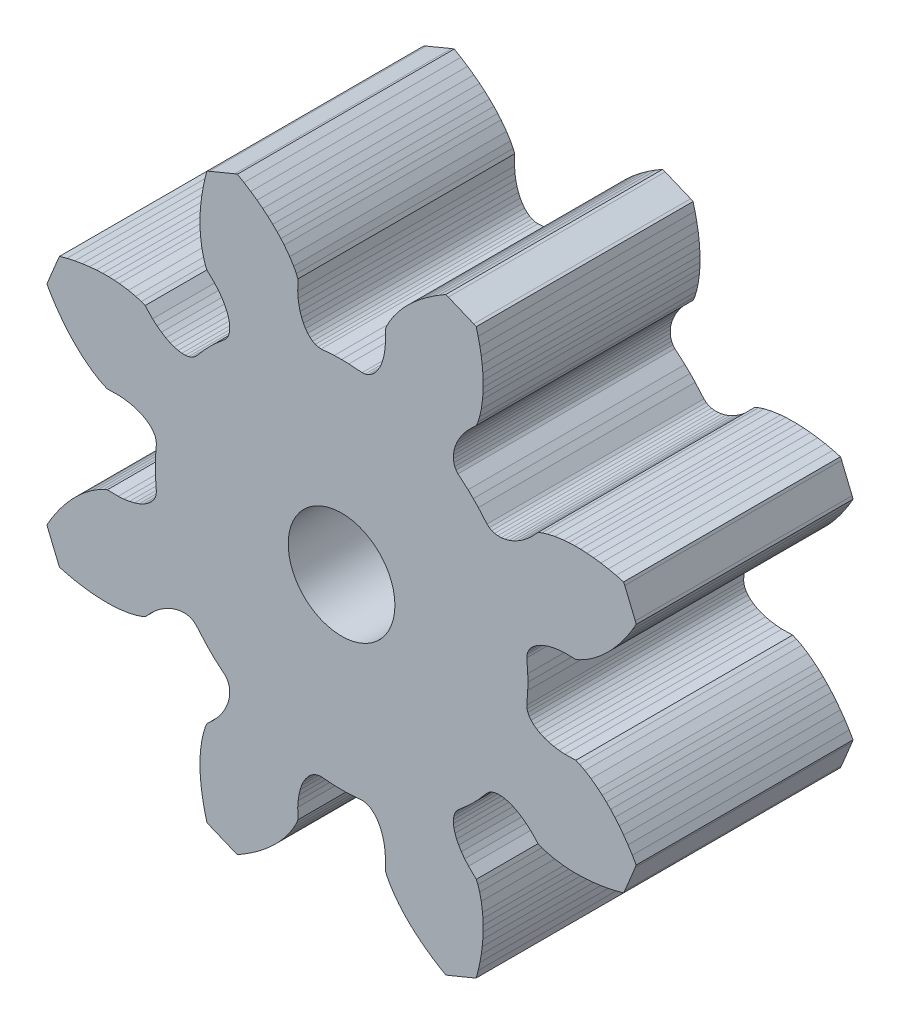
SolidWorks part; units mm, degrees
ref_plane "Front Plane" through (0, 0, 0) normal (0, 0, 1) x (1, 0, 0)
ref_plane "Top Plane" through (0, 0, 0) normal (0, 1, 0) x (1, 0, 0)
ref_plane "Right Plane" through (0, 0, 0) normal (1, 0, 0) x (0, 0, -1)
sketch "Sketch1" plane through (0, 0, 0) normal (0, 0, 1) x (1, 0, 0)
  line L472 (-0.6593, 18.6218) -> (-0.6593, 18.3271) construction
  line L473 (-0.6593, 18.3271) -> (-0.779, 17.4419) construction
  line L474 (-0.779, 17.4419) -> (-1.1197, 16.342) construction
  line L475 (-1.1197, 16.342) -> (-1.6601, 15.3477) construction
  line L476 (-1.6601, 15.3477) -> (-2.3747, 14.4808) construction
  line L477 (-2.3747, 14.4808) -> (-3.2417, 13.7653) construction
  line L478 (-3.2417, 13.7653) -> (-4.2368, 13.2249) construction
  line L479 (-4.2368, 13.2249) -> (-5.3358, 12.8842) construction
  line L480 (-5.3358, 12.8842) -> (-6.2209, 12.7645) construction
  line L481 (-6.2209, 12.7645) -> (-6.5158, 12.7645) construction
  line L482 (-6.5158, 12.7645) -> (-6.8114, 12.7645) construction
  line L483 (-6.8114, 12.7645) -> (-7.6964, 12.8842) construction
  line L484 (-7.6964, 12.8842) -> (-8.7961, 13.2249) construction
  line L485 (-8.7961, 13.2249) -> (-9.7913, 13.7653) construction
  line L486 (-9.7913, 13.7653) -> (-10.6581, 14.4808) construction
  line L487 (-10.6581, 14.4808) -> (-11.3729, 15.3477) construction
  line L488 (-11.3729, 15.3477) -> (-11.9132, 16.342) construction
  line L489 (-11.9132, 16.342) -> (-12.2541, 17.4419) construction
  line L490 (-12.2541, 17.4419) -> (-12.3729, 18.3271) construction
  line L491 (-12.3729, 18.3271) -> (-12.3729, 18.6218) construction
  line L492 (-12.3729, 18.6218) -> (-12.3729, 18.9172) construction
  line L493 (-12.3729, 18.9172) -> (-12.2541, 19.8023) construction
  line L494 (-12.2541, 19.8023) -> (-11.9132, 20.9013) construction
  line L495 (-11.9132, 20.9013) -> (-11.3729, 21.8965) construction
  line L496 (-11.3729, 21.8965) -> (-10.6581, 22.7634) construction
  line L497 (-10.6581, 22.7634) -> (-9.7913, 23.478) construction
  line L498 (-9.7913, 23.478) -> (-8.7961, 24.0184) construction
  line L499 (-8.7961, 24.0184) -> (-7.6964, 24.3591) construction
  line L500 (-7.6964, 24.3591) -> (-6.8114, 24.478) construction
  line L501 (-6.8114, 24.478) -> (-6.5158, 24.478) construction
  line L502 (-6.5158, 24.478) -> (-6.2209, 24.478) construction
  line L503 (-6.2209, 24.478) -> (-5.3358, 24.3591) construction
  line L504 (-5.3358, 24.3591) -> (-4.2368, 24.0184) construction
  line L505 (-4.2368, 24.0184) -> (-3.2417, 23.478) construction
  line L506 (-3.2417, 23.478) -> (-2.3747, 22.7634) construction
  line L507 (-2.3747, 22.7634) -> (-1.6601, 21.8965) construction
  line L508 (-1.6601, 21.8965) -> (-1.1197, 20.9013) construction
  line L509 (-1.1197, 20.9013) -> (-0.779, 19.8023) construction
  line L510 (-0.779, 19.8023) -> (-0.6593, 18.9172) construction
  line L511 (-0.6593, 18.9172) -> (-0.6593, 18.6218) construction
  line L512 (0.8049, 18.6218) -> (0.8049, 18.2532) construction
  line L513 (0.8049, 18.2532) -> (0.6559, 17.1463) construction
  line L514 (0.6559, 17.1463) -> (0.2287, 15.7724) construction
  line L515 (0.2287, 15.7724) -> (-0.4463, 14.5284) construction
  line L516 (-0.4463, 14.5284) -> (-1.34, 13.4451) construction
  line L517 (-1.34, 13.4451) -> (-2.4232, 12.5515) construction
  line L518 (-2.4232, 12.5515) -> (-3.6665, 11.8763) construction
  line L519 (-3.6665, 11.8763) -> (-5.0411, 11.4492) construction
  line L520 (-5.0411, 11.4492) -> (-6.1473, 11.3003) construction
  line L521 (-6.1473, 11.3003) -> (-6.5158, 11.3003) construction
  line L522 (-6.5158, 11.3003) -> (-6.885, 11.3003) construction
  line L523 (-6.885, 11.3003) -> (-7.9919, 11.4492) construction
  line L524 (-7.9919, 11.4492) -> (-9.3657, 11.8763) construction
  line L525 (-9.3657, 11.8763) -> (-10.6098, 12.5515) construction
  line L526 (-10.6098, 12.5515) -> (-11.693, 13.4451) construction
  line L527 (-11.693, 13.4451) -> (-12.5867, 14.5284) construction
  line L528 (-12.5867, 14.5284) -> (-13.2618, 15.7724) construction
  line L529 (-13.2618, 15.7724) -> (-13.689, 17.1463) construction
  line L530 (-13.689, 17.1463) -> (-13.837, 18.2532) construction
  line L531 (-13.837, 18.2532) -> (-13.837, 18.6218) construction
  line L532 (-13.837, 18.6218) -> (-13.837, 18.9908) construction
  line L533 (-13.837, 18.9908) -> (-13.689, 20.0979) construction
  line L534 (-13.689, 20.0979) -> (-13.2618, 21.4718) construction
  line L535 (-13.2618, 21.4718) -> (-12.5867, 22.7149) construction
  line L536 (-12.5867, 22.7149) -> (-11.693, 23.7989) construction
  line L537 (-11.693, 23.7989) -> (-10.6098, 24.6927) construction
  line L538 (-10.6098, 24.6927) -> (-9.3657, 25.3677) construction
  line L539 (-9.3657, 25.3677) -> (-7.9919, 25.794) construction
  line L540 (-7.9919, 25.794) -> (-6.885, 25.9421) construction
  line L541 (-6.885, 25.9421) -> (-6.5158, 25.9421) construction
  line L542 (-6.5158, 25.9421) -> (-6.1473, 25.9421) construction
  line L543 (-6.1473, 25.9421) -> (-5.0411, 25.794) construction
  line L544 (-5.0411, 25.794) -> (-3.6665, 25.3677) construction
  line L545 (-3.6665, 25.3677) -> (-2.4232, 24.6927) construction
  line L546 (-2.4232, 24.6927) -> (-1.34, 23.7989) construction
  line L547 (-1.34, 23.7989) -> (-0.4463, 22.7149) construction
  line L548 (-0.4463, 22.7149) -> (0.2287, 21.4718) construction
  line L549 (0.2287, 21.4718) -> (0.6559, 20.0979) construction
  line L550 (0.6559, 20.0979) -> (0.8049, 18.9908) construction
  line L551 (0.8049, 18.9908) -> (0.8049, 18.6218) construction
  line L576 (-9.7161, 12.1885) -> (-9.7564, 12.3731)
  line L577 (-9.7564, 12.3731) -> (-9.7872, 12.5499)
  line L578 (-9.7872, 12.5499) -> (-9.8096, 12.7171)
  line L579 (-9.8096, 12.7171) -> (-9.8246, 12.8763)
  line L580 (-9.8246, 12.8763) -> (-9.8316, 13.026)
  line L581 (-9.8316, 13.026) -> (-9.8325, 13.1663)
  line L582 (-9.8325, 13.1663) -> (-9.8278, 13.297)
  line L583 (-9.8278, 13.297) -> (-9.8183, 13.4183)
  line L584 (-9.8183, 13.4183) -> (-9.7888, 13.629)
  line L585 (-9.7888, 13.629) -> (-9.7501, 13.7986)
  line L586 (-9.7501, 13.7986) -> (-9.7098, 13.9285)
  line L587 (-9.7098, 13.9285) -> (-9.6724, 14.0181)
  line L588 (-9.6724, 14.0181) -> (-9.4909, 14.1939)
  line L589 (-9.4909, 14.1939) -> (-9.3999, 14.2985)
  line L590 (-9.3999, 14.2985) -> (-9.3229, 14.4023)
  line L591 (-9.3229, 14.4023) -> (-9.2604, 14.5046)
  line L592 (-9.2604, 14.5046) -> (-9.2106, 14.6045)
  line L593 (-9.2106, 14.6045) -> (-9.1732, 14.7011)
  line L594 (-9.1732, 14.7011) -> (-9.1487, 14.793)
  line L595 (-9.1487, 14.793) -> (-9.1367, 14.8802)
  line L596 (-9.1367, 14.8802) -> (-9.136, 14.961)
  line L597 (-9.136, 14.961) -> (-9.1462, 15.0347)
  line L598 (-9.1462, 15.0347) -> (-9.1678, 15.1012)
  line L599 (-9.1678, 15.1012) -> (-9.1987, 15.1599)
  line L600 (-9.1987, 15.1599) -> (-9.2438, 15.2145)
  line L601 (-9.2438, 15.2145) -> (-9.4792, 15.4174)
  line L602 (-9.4792, 15.4174) -> (-9.6019, 15.5362)
  line L603 (-9.6019, 15.5362) -> (-9.7199, 15.6591)
  line L604 (-9.7199, 15.6591) -> (-9.9236, 15.8936)
  line L605 (-9.9236, 15.8936) -> (-9.9784, 15.9395)
  line L606 (-9.9784, 15.9395) -> (-10.0361, 15.9704)
  line L607 (-10.0361, 15.9704) -> (-10.1027, 15.991)
  line L608 (-10.1027, 15.991) -> (-10.1763, 16.0014)
  line L609 (-10.1763, 16.0014) -> (-10.2572, 16.0014)
  line L610 (-10.2572, 16.0014) -> (-10.3445, 15.9887)
  line L611 (-10.3445, 15.9887) -> (-10.4364, 15.9642)
  line L612 (-10.4364, 15.9642) -> (-10.5329, 15.9276)
  line L613 (-10.5329, 15.9276) -> (-10.6327, 15.8777)
  line L614 (-10.6327, 15.8777) -> (-10.7349, 15.8143)
  line L615 (-10.7349, 15.8143) -> (-10.8396, 15.7375)
  line L616 (-10.8396, 15.7375) -> (-10.9435, 15.6472)
  line L617 (-10.9435, 15.6472) -> (-11.1193, 15.465)
  line L618 (-11.1193, 15.465) -> (-11.2089, 15.4285)
  line L619 (-11.2089, 15.4285) -> (-11.3388, 15.3873)
  line L620 (-11.3388, 15.3873) -> (-11.5084, 15.3484)
  line L621 (-11.5084, 15.3484) -> (-11.72, 15.3191)
  line L622 (-11.72, 15.3191) -> (-11.8405, 15.3096)
  line L623 (-11.8405, 15.3096) -> (-11.9711, 15.3049)
  line L624 (-11.9711, 15.3049) -> (-12.1113, 15.3065)
  line L625 (-12.1113, 15.3065) -> (-12.2611, 15.3135)
  line L626 (-12.2611, 15.3135) -> (-12.4203, 15.3278)
  line L627 (-12.4203, 15.3278) -> (-12.5883, 15.35)
  line L628 (-12.5883, 15.35) -> (-12.7643, 15.381)
  line L629 (-12.7643, 15.381) -> (-12.9487, 15.4213)
  line L630 (-12.9487, 15.4213) -> (-13.1224, 15.4673)
  line L631 (-13.1224, 15.4673) -> (-13.1503, 15.5259)
  line L632 (-13.1503, 15.5259) -> (-13.3965, 16.1201)
  line L633 (-13.3965, 16.1201) -> (-13.418, 16.1805)
  line L634 (-13.418, 16.1805) -> (-13.3277, 16.3357)
  line L635 (-13.3277, 16.3357) -> (-13.2264, 16.495)
  line L636 (-13.2264, 16.495) -> (-13.1232, 16.6415)
  line L637 (-13.1232, 16.6415) -> (-13.0201, 16.7755)
  line L638 (-13.0201, 16.7755) -> (-12.9179, 16.8983)
  line L639 (-12.9179, 16.8983) -> (-12.8173, 17.0093)
  line L640 (-12.8173, 17.0093) -> (-12.7184, 17.109)
  line L641 (-12.7184, 17.109) -> (-12.6224, 17.1986)
  line L642 (-12.6224, 17.1986) -> (-12.5306, 17.2771)
  line L643 (-12.5306, 17.2771) -> (-12.3609, 17.4055)
  line L644 (-12.3609, 17.4055) -> (-12.2135, 17.4982)
  line L645 (-12.2135, 17.4982) -> (-12.0924, 17.5606)
  line L646 (-12.0924, 17.5606) -> (-12.0035, 17.5989)
  line L647 (-12.0035, 17.5989) -> (-11.75, 17.5939)
  line L648 (-11.75, 17.5939) -> (-11.6122, 17.6043)
  line L649 (-11.6122, 17.6043) -> (-11.4847, 17.6234)
  line L650 (-11.4847, 17.6234) -> (-11.3672, 17.651)
  line L651 (-11.3672, 17.651) -> (-11.2619, 17.6858)
  line L652 (-11.2619, 17.6858) -> (-11.1677, 17.7278)
  line L653 (-11.1677, 17.7278) -> (-11.0853, 17.7763)
  line L654 (-11.0853, 17.7763) -> (-11.0146, 17.8285)
  line L655 (-11.0146, 17.8285) -> (-10.9569, 17.8856)
  line L656 (-10.9569, 17.8856) -> (-10.9116, 17.9459)
  line L657 (-10.9116, 17.9459) -> (-10.88, 18.0075)
  line L658 (-10.88, 18.0075) -> (-10.861, 18.0702)
  line L659 (-10.861, 18.0702) -> (-10.8547, 18.1408)
  line L660 (-10.8547, 18.1408) -> (-10.8769, 18.4513)
  line L661 (-10.8769, 18.4513) -> (-10.88, 18.6218)
  line L662 (-10.88, 18.6218) -> (-10.8769, 18.7919)
  line L663 (-10.8769, 18.7919) -> (-10.8547, 19.1018)
  line L664 (-10.8547, 19.1018) -> (-10.861, 19.1731)
  line L665 (-10.861, 19.1731) -> (-10.88, 19.2358)
  line L666 (-10.88, 19.2358) -> (-10.9116, 19.2977)
  line L667 (-10.9116, 19.2977) -> (-10.9569, 19.3579)
  line L668 (-10.9569, 19.3579) -> (-11.0146, 19.4141)
  line L669 (-11.0146, 19.4141) -> (-11.0853, 19.4673)
  line L670 (-11.0853, 19.4673) -> (-11.1677, 19.5147)
  line L671 (-11.1677, 19.5147) -> (-11.2619, 19.5566)
  line L672 (-11.2619, 19.5566) -> (-11.3672, 19.5924)
  line L673 (-11.3672, 19.5924) -> (-11.4847, 19.6202)
  line L674 (-11.4847, 19.6202) -> (-11.6122, 19.639)
  line L675 (-11.6122, 19.639) -> (-11.75, 19.6485)
  line L676 (-11.75, 19.6485) -> (-12.0035, 19.6447)
  line L677 (-12.0035, 19.6447) -> (-12.0924, 19.6818)
  line L678 (-12.0924, 19.6818) -> (-12.2135, 19.7453)
  line L679 (-12.2135, 19.7453) -> (-12.3609, 19.8381)
  line L680 (-12.3609, 19.8381) -> (-12.5306, 19.9664)
  line L681 (-12.5306, 19.9664) -> (-12.6224, 20.0447)
  line L682 (-12.6224, 20.0447) -> (-12.7184, 20.1344)
  line L683 (-12.7184, 20.1344) -> (-12.8173, 20.2333)
  line L684 (-12.8173, 20.2333) -> (-12.9179, 20.3443)
  line L685 (-12.9179, 20.3443) -> (-13.0201, 20.4678)
  line L686 (-13.0201, 20.4678) -> (-13.1232, 20.6018)
  line L687 (-13.1232, 20.6018) -> (-13.2264, 20.7484)
  line L688 (-13.2264, 20.7484) -> (-13.3277, 20.9076)
  line L689 (-13.3277, 20.9076) -> (-13.418, 21.0621)
  line L690 (-13.418, 21.0621) -> (-13.3965, 21.1233)
  line L691 (-13.3965, 21.1233) -> (-13.1503, 21.7181)
  line L692 (-13.1503, 21.7181) -> (-13.1224, 21.776)
  line L693 (-13.1224, 21.776) -> (-12.9487, 21.822)
  line L694 (-12.9487, 21.822) -> (-12.7643, 21.8624)
  line L695 (-12.7643, 21.8624) -> (-12.5883, 21.8934)
  line L696 (-12.5883, 21.8934) -> (-12.4203, 21.9154)
  line L697 (-12.4203, 21.9154) -> (-12.2611, 21.9298)
  line L698 (-12.2611, 21.9298) -> (-12.1113, 21.9368)
  line L699 (-12.1113, 21.9368) -> (-11.9711, 21.9376)
  line L700 (-11.9711, 21.9376) -> (-11.8405, 21.933)
  line L701 (-11.8405, 21.933) -> (-11.72, 21.9242)
  line L702 (-11.72, 21.9242) -> (-11.5084, 21.894)
  line L703 (-11.5084, 21.894) -> (-11.3388, 21.8562)
  line L704 (-11.3388, 21.8562) -> (-11.2089, 21.815)
  line L705 (-11.2089, 21.815) -> (-11.1193, 21.7785)
  line L706 (-11.1193, 21.7785) -> (-10.9435, 21.5962)
  line L707 (-10.9435, 21.5962) -> (-10.8396, 21.5058)
  line L708 (-10.8396, 21.5058) -> (-10.7349, 21.429)
  line L709 (-10.7349, 21.429) -> (-10.6327, 21.3656)
  line L710 (-10.6327, 21.3656) -> (-10.5329, 21.3158)
  line L711 (-10.5329, 21.3158) -> (-10.4364, 21.2784)
  line L712 (-10.4364, 21.2784) -> (-10.3445, 21.2547)
  line L713 (-10.3445, 21.2547) -> (-10.2572, 21.242)
  line L714 (-10.2572, 21.242) -> (-10.1763, 21.2413)
  line L715 (-10.1763, 21.2413) -> (-10.1027, 21.2522)
  line L716 (-10.1027, 21.2522) -> (-10.0361, 21.2728)
  line L717 (-10.0361, 21.2728) -> (-9.9784, 21.3038)
  line L718 (-9.9784, 21.3038) -> (-9.9236, 21.3498)
  line L719 (-9.9236, 21.3498) -> (-9.7199, 21.5842)
  line L720 (-9.7199, 21.5842) -> (-9.6019, 21.7072)
  line L721 (-9.6019, 21.7072) -> (-9.4792, 21.8252)
  line L722 (-9.4792, 21.8252) -> (-9.2438, 22.0289)
  line L723 (-9.2438, 22.0289) -> (-9.1987, 22.0836)
  line L724 (-9.1987, 22.0836) -> (-9.1678, 22.1412)
  line L725 (-9.1678, 22.1412) -> (-9.1462, 22.2078)
  line L726 (-9.1462, 22.2078) -> (-9.136, 22.2825)
  line L727 (-9.136, 22.2825) -> (-9.1367, 22.3632)
  line L728 (-9.1367, 22.3632) -> (-9.1487, 22.4504)
  line L729 (-9.1487, 22.4504) -> (-9.1732, 22.5423)
  line L730 (-9.1732, 22.5423) -> (-9.2106, 22.6388)
  line L731 (-9.2106, 22.6388) -> (-9.2604, 22.7389)
  line L732 (-9.2604, 22.7389) -> (-9.3229, 22.841)
  line L733 (-9.3229, 22.841) -> (-9.3999, 22.9448)
  line L734 (-9.3999, 22.9448) -> (-9.4909, 23.0494)
  line L735 (-9.4909, 23.0494) -> (-9.6724, 23.2254)
  line L736 (-9.6724, 23.2254) -> (-9.7098, 23.3147)
  line L737 (-9.7098, 23.3147) -> (-9.7501, 23.4447)
  line L738 (-9.7501, 23.4447) -> (-9.7888, 23.6143)
  line L739 (-9.7888, 23.6143) -> (-9.8183, 23.8252)
  line L740 (-9.8183, 23.8252) -> (-9.8278, 23.9455)
  line L741 (-9.8278, 23.9455) -> (-9.8325, 24.0771)
  line L742 (-9.8325, 24.0771) -> (-9.8316, 24.2175)
  line L743 (-9.8316, 24.2175) -> (-9.8246, 24.3663)
  line L744 (-9.8246, 24.3663) -> (-9.8096, 24.5263)
  line L745 (-9.8096, 24.5263) -> (-9.7872, 24.6934)
  line L746 (-9.7872, 24.6934) -> (-9.7564, 24.8701)
  line L747 (-9.7564, 24.8701) -> (-9.7161, 25.0542)
  line L748 (-9.7161, 25.0542) -> (-9.6708, 25.2284)
  line L749 (-9.6708, 25.2284) -> (-9.613, 25.2561)
  line L750 (-9.613, 25.2561) -> (-9.0178, 25.5027)
  line L751 (-9.0178, 25.5027) -> (-8.9571, 25.5238)
  line L752 (-8.9571, 25.5238) -> (-8.8017, 25.4329)
  line L753 (-8.8017, 25.4329) -> (-8.6432, 25.3314)
  line L754 (-8.6432, 25.3314) -> (-8.4966, 25.2284)
  line L755 (-8.4966, 25.2284) -> (-8.3619, 25.1262)
  line L756 (-8.3619, 25.1262) -> (-8.2391, 25.023)
  line L757 (-8.2391, 25.023) -> (-8.1283, 24.9224)
  line L758 (-8.1283, 24.9224) -> (-8.0284, 24.8243)
  line L759 (-8.0284, 24.8243) -> (-7.9387, 24.7283)
  line L760 (-7.9387, 24.7283) -> (-7.8603, 24.6365)
  line L761 (-7.8603, 24.6365) -> (-7.732, 24.466)
  line L762 (-7.732, 24.466) -> (-7.6393, 24.3188)
  line L763 (-7.6393, 24.3188) -> (-7.5767, 24.1983)
  line L764 (-7.5767, 24.1983) -> (-7.5394, 24.1086)
  line L765 (-7.5394, 24.1086) -> (-7.5434, 23.856)
  line L766 (-7.5434, 23.856) -> (-7.5339, 23.7183)
  line L767 (-7.5339, 23.7183) -> (-7.514, 23.5897)
  line L768 (-7.514, 23.5897) -> (-7.4873, 23.4733)
  line L769 (-7.4873, 23.4733) -> (-7.4515, 23.367)
  line L770 (-7.4515, 23.367) -> (-7.4096, 23.2728)
  line L771 (-7.4096, 23.2728) -> (-7.3611, 23.1904)
  line L772 (-7.3611, 23.1904) -> (-7.3089, 23.1198)
  line L773 (-7.3089, 23.1198) -> (-7.2517, 23.0628)
  line L774 (-7.2517, 23.0628) -> (-7.1923, 23.0178)
  line L775 (-7.1923, 23.0178) -> (-7.1306, 22.9851)
  line L776 (-7.1306, 22.9851) -> (-7.0671, 22.9663)
  line L777 (-7.0671, 22.9663) -> (-6.9967, 22.9597)
  line L778 (-6.9967, 22.9597) -> (-6.6868, 22.982)
  line L779 (-6.6868, 22.982) -> (-6.5158, 22.9851)
  line L780 (-6.5158, 22.9851) -> (-6.3455, 22.982)
  line L781 (-6.3455, 22.982) -> (-6.0354, 22.9597)
  line L782 (-6.0354, 22.9597) -> (-5.965, 22.9663)
  line L783 (-5.965, 22.9663) -> (-5.9016, 22.9851)
  line L784 (-5.9016, 22.9851) -> (-5.8397, 23.0178)
  line L785 (-5.8397, 23.0178) -> (-5.7806, 23.0628)
  line L786 (-5.7806, 23.0628) -> (-5.7233, 23.1198)
  line L787 (-5.7233, 23.1198) -> (-5.6703, 23.1904)
  line L788 (-5.6703, 23.1904) -> (-5.6227, 23.2728)
  line L789 (-5.6227, 23.2728) -> (-5.5808, 23.367)
  line L790 (-5.5808, 23.367) -> (-5.545, 23.4733)
  line L791 (-5.545, 23.4733) -> (-5.5174, 23.5897)
  line L792 (-5.5174, 23.5897) -> (-5.4984, 23.7183)
  line L793 (-5.4984, 23.7183) -> (-5.4888, 23.856)
  line L794 (-5.4888, 23.856) -> (-5.4928, 24.1086)
  line L795 (-5.4928, 24.1086) -> (-5.4556, 24.1983)
  line L796 (-5.4556, 24.1983) -> (-5.3928, 24.3188)
  line L797 (-5.3928, 24.3188) -> (-5.3002, 24.466)
  line L798 (-5.3002, 24.466) -> (-5.172, 24.6365)
  line L799 (-5.172, 24.6365) -> (-5.0927, 24.7283)
  line L800 (-5.0927, 24.7283) -> (-5.0037, 24.8243)
  line L801 (-5.0037, 24.8243) -> (-4.904, 24.9224)
  line L802 (-4.904, 24.9224) -> (-4.793, 25.023)
  line L803 (-4.793, 25.023) -> (-4.6703, 25.1262)
  line L804 (-4.6703, 25.1262) -> (-4.5356, 25.2284)
  line L805 (-4.5356, 25.2284) -> (-4.389, 25.3314)
  line L806 (-4.389, 25.3314) -> (-4.2306, 25.4329)
  line L807 (-4.2306, 25.4329) -> (-4.0752, 25.5238)
  line L808 (-4.0752, 25.5238) -> (-4.015, 25.5027)
  line L809 (-4.015, 25.5027) -> (-3.42, 25.2561)
  line L810 (-3.42, 25.2561) -> (-3.3614, 25.2284)
  line L811 (-3.3614, 25.2284) -> (-3.3162, 25.0542)
  line L812 (-3.3162, 25.0542) -> (-3.2758, 24.8701)
  line L813 (-3.2758, 24.8701) -> (-3.2442, 24.6934)
  line L814 (-3.2442, 24.6934) -> (-3.2218, 24.5263)
  line L815 (-3.2218, 24.5263) -> (-3.2076, 24.3663)
  line L816 (-3.2076, 24.3663) -> (-3.2005, 24.2175)
  line L817 (-3.2005, 24.2175) -> (-3.1998, 24.0771)
  line L818 (-3.1998, 24.0771) -> (-3.2044, 23.9455)
  line L819 (-3.2044, 23.9455) -> (-3.2139, 23.8252)
  line L820 (-3.2139, 23.8252) -> (-3.2433, 23.6143)
  line L821 (-3.2433, 23.6143) -> (-3.2812, 23.4447)
  line L822 (-3.2812, 23.4447) -> (-3.3224, 23.3147)
  line L823 (-3.3224, 23.3147) -> (-3.3598, 23.2254)
  line L824 (-3.3598, 23.2254) -> (-3.5411, 23.0494)
  line L825 (-3.5411, 23.0494) -> (-3.6323, 22.9448)
  line L826 (-3.6323, 22.9448) -> (-3.7084, 22.841)
  line L827 (-3.7084, 22.841) -> (-3.7717, 22.7389)
  line L828 (-3.7717, 22.7389) -> (-3.8216, 22.6388)
  line L829 (-3.8216, 22.6388) -> (-3.859, 22.5423)
  line L830 (-3.859, 22.5423) -> (-3.8835, 22.4504)
  line L831 (-3.8835, 22.4504) -> (-3.8955, 22.3632)
  line L832 (-3.8955, 22.3632) -> (-3.8961, 22.2825)
  line L833 (-3.8961, 22.2825) -> (-3.8859, 22.2078)
  line L834 (-3.8859, 22.2078) -> (-3.8644, 22.1412)
  line L835 (-3.8644, 22.1412) -> (-3.8336, 22.0836)
  line L836 (-3.8336, 22.0836) -> (-3.7883, 22.0289)
  line L837 (-3.7883, 22.0289) -> (-3.553, 21.8252)
  line L838 (-3.553, 21.8252) -> (-3.4304, 21.7072)
  line L839 (-3.4304, 21.7072) -> (-3.3124, 21.5842)
  line L840 (-3.3124, 21.5842) -> (-3.1086, 21.3498)
  line L841 (-3.1086, 21.3498) -> (-3.0539, 21.3038)
  line L842 (-3.0539, 21.3038) -> (-2.996, 21.2728)
  line L843 (-2.996, 21.2728) -> (-2.9296, 21.2522)
  line L844 (-2.9296, 21.2522) -> (-2.856, 21.2413)
  line L845 (-2.856, 21.2413) -> (-2.7742, 21.242)
  line L846 (-2.7742, 21.242) -> (-2.6877, 21.2547)
  line L847 (-2.6877, 21.2547) -> (-2.595, 21.2784)
  line L848 (-2.595, 21.2784) -> (-2.4993, 21.3158)
  line L849 (-2.4993, 21.3158) -> (-2.3996, 21.3656)
  line L850 (-2.3996, 21.3656) -> (-2.2964, 21.429)
  line L851 (-2.2964, 21.429) -> (-2.1926, 21.5058)
  line L852 (-2.1926, 21.5058) -> (-2.0879, 21.5962)
  line L853 (-2.0879, 21.5962) -> (-1.9129, 21.7785)
  line L854 (-1.9129, 21.7785) -> (-1.8234, 21.815)
  line L855 (-1.8234, 21.815) -> (-1.6934, 21.8562)
  line L856 (-1.6934, 21.8562) -> (-1.523, 21.894)
  line L857 (-1.523, 21.894) -> (-1.3122, 21.9242)
  line L858 (-1.3122, 21.9242) -> (-1.1917, 21.933)
  line L859 (-1.1917, 21.933) -> (-1.0612, 21.9376)
  line L860 (-1.0612, 21.9376) -> (-0.9208, 21.9368)
  line L861 (-0.9208, 21.9368) -> (-0.7711, 21.9298)
  line L862 (-0.7711, 21.9298) -> (-0.6111, 21.9154)
  line L863 (-0.6111, 21.9154) -> (-0.4438, 21.8934)
  line L864 (-0.4438, 21.8934) -> (-0.268, 21.8624)
  line L865 (-0.268, 21.8624) -> (-0.0834, 21.822)
  line L866 (-0.0834, 21.822) -> (0.0903, 21.776)
  line L867 (0.0903, 21.776) -> (0.118, 21.7181)
  line L868 (0.118, 21.7181) -> (0.3642, 21.1233)
  line L869 (0.3642, 21.1233) -> (0.3857, 21.0621)
  line L870 (0.3857, 21.0621) -> (0.2955, 20.9076)
  line L871 (0.2955, 20.9076) -> (0.1941, 20.7484)
  line L872 (0.1941, 20.7484) -> (0.091, 20.6018)
  line L873 (0.091, 20.6018) -> (-0.012, 20.4678)
  line L874 (-0.012, 20.4678) -> (-0.1142, 20.3443)
  line L875 (-0.1142, 20.3443) -> (-0.2148, 20.2333)
  line L876 (-0.2148, 20.2333) -> (-0.3139, 20.1344)
  line L877 (-0.3139, 20.1344) -> (-0.4098, 20.0447)
  line L878 (-0.4098, 20.0447) -> (-0.5017, 19.9664)
  line L879 (-0.5017, 19.9664) -> (-0.6712, 19.8381)
  line L880 (-0.6712, 19.8381) -> (-0.8187, 19.7453)
  line L881 (-0.8187, 19.7453) -> (-0.9398, 19.6818)
  line L882 (-0.9398, 19.6818) -> (-1.0286, 19.6447)
  line L883 (-1.0286, 19.6447) -> (-1.2823, 19.6485)
  line L884 (-1.2823, 19.6485) -> (-1.42, 19.639)
  line L885 (-1.42, 19.639) -> (-1.5475, 19.6202)
  line L886 (-1.5475, 19.6202) -> (-1.6648, 19.5924)
  line L887 (-1.6648, 19.5924) -> (-1.7702, 19.5566)
  line L888 (-1.7702, 19.5566) -> (-1.8646, 19.5147)
  line L889 (-1.8646, 19.5147) -> (-1.947, 19.4673)
  line L890 (-1.947, 19.4673) -> (-2.0175, 19.4141)
  line L891 (-2.0175, 19.4141) -> (-2.0753, 19.3579)
  line L892 (-2.0753, 19.3579) -> (-2.1197, 19.2977)
  line L893 (-2.1197, 19.2977) -> (-2.1522, 19.2358)
  line L894 (-2.1522, 19.2358) -> (-2.1713, 19.1731)
  line L895 (-2.1713, 19.1731) -> (-2.1776, 19.1018)
  line L896 (-2.1776, 19.1018) -> (-2.1552, 18.7919)
  line L897 (-2.1552, 18.7919) -> (-2.1522, 18.6218)
  line L898 (-2.1522, 18.6218) -> (-2.1552, 18.4513)
  line L899 (-2.1552, 18.4513) -> (-2.1776, 18.1408)
  line L900 (-2.1776, 18.1408) -> (-2.1713, 18.0702)
  line L901 (-2.1713, 18.0702) -> (-2.1522, 18.0075)
  line L902 (-2.1522, 18.0075) -> (-2.1197, 17.9459)
  line L903 (-2.1197, 17.9459) -> (-2.0753, 17.8856)
  line L904 (-2.0753, 17.8856) -> (-2.0175, 17.8285)
  line L905 (-2.0175, 17.8285) -> (-1.947, 17.7763)
  line L906 (-1.947, 17.7763) -> (-1.8646, 17.7278)
  line L907 (-1.8646, 17.7278) -> (-1.7702, 17.6858)
  line L908 (-1.7702, 17.6858) -> (-1.6648, 17.651)
  line L909 (-1.6648, 17.651) -> (-1.5475, 17.6234)
  line L910 (-1.5475, 17.6234) -> (-1.42, 17.6043)
  line L911 (-1.42, 17.6043) -> (-1.2823, 17.5939)
  line L912 (-1.2823, 17.5939) -> (-1.0286, 17.5989)
  line L913 (-1.0286, 17.5989) -> (-0.9398, 17.5606)
  line L914 (-0.9398, 17.5606) -> (-0.8187, 17.4982)
  line L915 (-0.8187, 17.4982) -> (-0.6712, 17.4055)
  line L916 (-0.6712, 17.4055) -> (-0.5017, 17.2771)
  line L917 (-0.5017, 17.2771) -> (-0.4098, 17.1986)
  line L918 (-0.4098, 17.1986) -> (-0.3139, 17.109)
  line L919 (-0.3139, 17.109) -> (-0.2148, 17.0093)
  line L920 (-0.2148, 17.0093) -> (-0.1142, 16.8983)
  line L921 (-0.1142, 16.8983) -> (-0.012, 16.7755)
  line L922 (-0.012, 16.7755) -> (0.091, 16.6415)
  line L923 (0.091, 16.6415) -> (0.1941, 16.495)
  line L924 (0.1941, 16.495) -> (0.2955, 16.3357)
  line L925 (0.2955, 16.3357) -> (0.3857, 16.1805)
  line L926 (0.3857, 16.1805) -> (0.3642, 16.1201)
  line L927 (0.3642, 16.1201) -> (0.118, 15.5259)
  line L928 (0.118, 15.5259) -> (0.0903, 15.4673)
  line L929 (0.0903, 15.4673) -> (-0.0834, 15.4213)
  line L930 (-0.0834, 15.4213) -> (-0.268, 15.381)
  line L931 (-0.268, 15.381) -> (-0.4438, 15.35)
  line L932 (-0.4438, 15.35) -> (-0.6111, 15.3278)
  line L933 (-0.6111, 15.3278) -> (-0.7711, 15.3135)
  line L934 (-0.7711, 15.3135) -> (-0.9208, 15.3065)
  line L935 (-0.9208, 15.3065) -> (-1.0612, 15.3049)
  line L936 (-1.0612, 15.3049) -> (-1.1917, 15.3096)
  line L937 (-1.1917, 15.3096) -> (-1.3122, 15.3191)
  line L938 (-1.3122, 15.3191) -> (-1.523, 15.3484)
  line L939 (-1.523, 15.3484) -> (-1.6934, 15.3873)
  line L940 (-1.6934, 15.3873) -> (-1.8234, 15.4285)
  line L941 (-1.8234, 15.4285) -> (-1.9129, 15.465)
  line L942 (-1.9129, 15.465) -> (-2.0879, 15.6472)
  line L943 (-2.0879, 15.6472) -> (-2.1926, 15.7375)
  line L944 (-2.1926, 15.7375) -> (-2.2964, 15.8143)
  line L945 (-2.2964, 15.8143) -> (-2.3996, 15.8777)
  line L946 (-2.3996, 15.8777) -> (-2.4993, 15.9276)
  line L947 (-2.4993, 15.9276) -> (-2.595, 15.9642)
  line L948 (-2.595, 15.9642) -> (-2.6877, 15.9887)
  line L949 (-2.6877, 15.9887) -> (-2.7742, 16.0014)
  line L950 (-2.7742, 16.0014) -> (-2.856, 16.0014)
  line L951 (-2.856, 16.0014) -> (-2.9296, 15.991)
  line L952 (-2.9296, 15.991) -> (-2.996, 15.9704)
  line L953 (-2.996, 15.9704) -> (-3.0539, 15.9395)
  line L954 (-3.0539, 15.9395) -> (-3.1086, 15.8936)
  line L955 (-3.1086, 15.8936) -> (-3.3124, 15.6591)
  line L956 (-3.3124, 15.6591) -> (-3.4304, 15.5362)
  line L957 (-3.4304, 15.5362) -> (-3.553, 15.4174)
  line L958 (-3.553, 15.4174) -> (-3.7883, 15.2145)
  line L959 (-3.7883, 15.2145) -> (-3.8336, 15.1599)
  line L960 (-3.8336, 15.1599) -> (-3.8644, 15.1012)
  line L961 (-3.8644, 15.1012) -> (-3.8859, 15.0347)
  line L962 (-3.8859, 15.0347) -> (-3.8961, 14.961)
  line L963 (-3.8961, 14.961) -> (-3.8955, 14.8802)
  line L964 (-3.8955, 14.8802) -> (-3.8835, 14.793)
  line L965 (-3.8835, 14.793) -> (-3.859, 14.7011)
  line L966 (-3.859, 14.7011) -> (-3.8216, 14.6045)
  line L967 (-3.8216, 14.6045) -> (-3.7717, 14.5046)
  line L968 (-3.7717, 14.5046) -> (-3.7084, 14.4023)
  line L969 (-3.7084, 14.4023) -> (-3.6323, 14.2985)
  line L970 (-3.6323, 14.2985) -> (-3.5411, 14.1939)
  line L971 (-3.5411, 14.1939) -> (-3.3598, 14.0181)
  line L972 (-3.3598, 14.0181) -> (-3.3224, 13.9285)
  line L973 (-3.3224, 13.9285) -> (-3.2812, 13.7986)
  line L974 (-3.2812, 13.7986) -> (-3.2433, 13.629)
  line L975 (-3.2433, 13.629) -> (-3.2139, 13.4183)
  line L976 (-3.2139, 13.4183) -> (-3.2044, 13.297)
  line L977 (-3.2044, 13.297) -> (-3.1998, 13.1663)
  line L978 (-3.1998, 13.1663) -> (-3.2005, 13.026)
  line L979 (-3.2005, 13.026) -> (-3.2076, 12.8763)
  line L980 (-3.2076, 12.8763) -> (-3.2218, 12.7171)
  line L981 (-3.2218, 12.7171) -> (-3.2442, 12.5499)
  line L982 (-3.2442, 12.5499) -> (-3.2758, 12.3731)
  line L983 (-3.2758, 12.3731) -> (-3.3162, 12.1885)
  line L984 (-3.3162, 12.1885) -> (-3.3614, 12.015)
  line L985 (-3.3614, 12.015) -> (-3.42, 11.9873)
  line L986 (-3.42, 11.9873) -> (-4.015, 11.7416)
  line L987 (-4.015, 11.7416) -> (-4.0752, 11.7194)
  line L988 (-4.0752, 11.7194) -> (-4.2306, 11.8098)
  line L989 (-4.2306, 11.8098) -> (-4.389, 11.9119)
  line L990 (-4.389, 11.9119) -> (-4.5356, 12.0142)
  line L991 (-4.5356, 12.0142) -> (-4.6703, 12.1173)
  line L992 (-4.6703, 12.1173) -> (-4.793, 12.2202)
  line L993 (-4.793, 12.2202) -> (-4.904, 12.3209)
  line L994 (-4.904, 12.3209) -> (-5.0037, 12.4191)
  line L995 (-5.0037, 12.4191) -> (-5.0927, 12.515)
  line L996 (-5.0927, 12.515) -> (-5.172, 12.6068)
  line L997 (-5.172, 12.6068) -> (-5.3002, 12.7773)
  line L998 (-5.3002, 12.7773) -> (-5.3928, 12.9239)
  line L999 (-5.3928, 12.9239) -> (-5.4556, 13.0451)
  line L1000 (-5.4556, 13.0451) -> (-5.4928, 13.1346)
  line L1001 (-5.4928, 13.1346) -> (-5.4888, 13.3873)
  line L1002 (-5.4888, 13.3873) -> (-5.4984, 13.5252)
  line L1003 (-5.4984, 13.5252) -> (-5.5174, 13.6528)
  line L1004 (-5.5174, 13.6528) -> (-5.545, 13.7701)
  line L1005 (-5.545, 13.7701) -> (-5.5808, 13.8763)
  line L1006 (-5.5808, 13.8763) -> (-5.6227, 13.9705)
  line L1007 (-5.6227, 13.9705) -> (-5.6703, 14.053)
  line L1008 (-5.6703, 14.053) -> (-5.7233, 14.1226)
  line L1009 (-5.7233, 14.1226) -> (-5.7806, 14.1805)
  line L1010 (-5.7806, 14.1805) -> (-5.8397, 14.2256)
  line L1011 (-5.8397, 14.2256) -> (-5.9016, 14.2573)
  line L1012 (-5.9016, 14.2573) -> (-5.965, 14.2772)
  line L1013 (-5.965, 14.2772) -> (-6.0354, 14.2834)
  line L1014 (-6.0354, 14.2834) -> (-6.3455, 14.2612)
  line L1015 (-6.3455, 14.2612) -> (-6.5158, 14.2573)
  line L1016 (-6.5158, 14.2573) -> (-6.6868, 14.2612)
  line L1017 (-6.6868, 14.2612) -> (-6.9967, 14.2834)
  line L1018 (-6.9967, 14.2834) -> (-7.0671, 14.2772)
  line L1019 (-7.0671, 14.2772) -> (-7.1306, 14.2573)
  line L1020 (-7.1306, 14.2573) -> (-7.1923, 14.2256)
  line L1021 (-7.1923, 14.2256) -> (-7.2517, 14.1805)
  line L1022 (-7.2517, 14.1805) -> (-7.3089, 14.1226)
  line L1023 (-7.3089, 14.1226) -> (-7.3611, 14.053)
  line L1024 (-7.3611, 14.053) -> (-7.4096, 13.9705)
  line L1025 (-7.4096, 13.9705) -> (-7.4515, 13.8763)
  line L1026 (-7.4515, 13.8763) -> (-7.4873, 13.7701)
  line L1027 (-7.4873, 13.7701) -> (-7.514, 13.6528)
  line L1028 (-7.514, 13.6528) -> (-7.5339, 13.5252)
  line L1029 (-7.5339, 13.5252) -> (-7.5434, 13.3873)
  line L1030 (-7.5434, 13.3873) -> (-7.5394, 13.1346)
  line L1031 (-7.5394, 13.1346) -> (-7.5767, 13.0451)
  line L1032 (-7.5767, 13.0451) -> (-7.6393, 12.9239)
  line L1033 (-7.6393, 12.9239) -> (-7.732, 12.7773)
  line L1034 (-7.732, 12.7773) -> (-7.8603, 12.6068)
  line L1035 (-7.8603, 12.6068) -> (-7.9387, 12.515)
  line L1036 (-7.9387, 12.515) -> (-8.0284, 12.4191)
  line L1037 (-8.0284, 12.4191) -> (-8.1283, 12.3209)
  line L1038 (-8.1283, 12.3209) -> (-8.2391, 12.2202)
  line L1039 (-8.2391, 12.2202) -> (-8.3619, 12.1173)
  line L1040 (-8.3619, 12.1173) -> (-8.4966, 12.0142)
  line L1041 (-8.4966, 12.0142) -> (-8.6432, 11.9119)
  line L1042 (-8.6432, 11.9119) -> (-8.8017, 11.8098)
  line L1043 (-8.8017, 11.8098) -> (-8.9571, 11.7194)
  line L1044 (-8.9571, 11.7194) -> (-9.0178, 11.7416)
  line L1045 (-9.0178, 11.7416) -> (-9.613, 11.9873)
  line L1046 (-9.613, 11.9873) -> (-9.6708, 12.015)
  line L1047 (-9.6708, 12.015) -> (-9.7161, 12.1885)
  line L1048 (-6.0298, 19.773) -> (-6.9252, 17.6545) construction
  line L1049 (-5.4572, 18.174) -> (-7.5759, 19.0694) construction
  circle A0 centre (-6.5166, 18.6217) radius 1.25
  dimension "D1" = 2.5
extrude "Boss-Extrude1" add sketch "Sketch1" along normal blind 5.08
